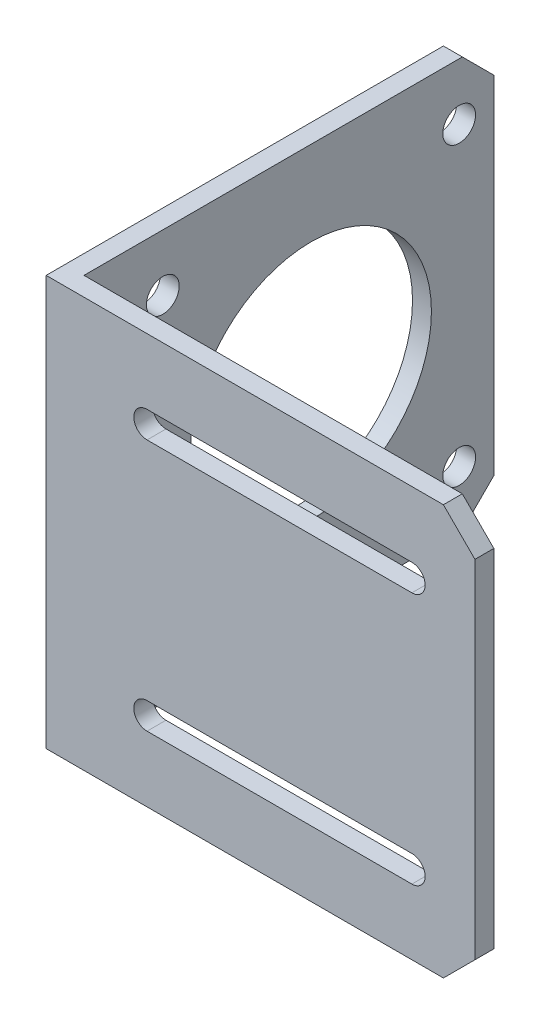
SolidWorks part; units mm, degrees
ref_plane "前视基准面" through (0, 0, 0) normal (0, 0, 1) x (1, 0, 0)
ref_plane "上视基准面" through (0, 0, 0) normal (0, 1, 0) x (1, 0, 0)
ref_plane "右视基准面" through (0, 0, 0) normal (1, 0, 0) x (0, 0, -1)
sketch "草图1" plane through (0, 0, 0) normal (0, 1, 0) x (1, 0, 0)
  line L1 (0, 0) -> (68, 0)
  line L2 (0, 0) -> (0, 3)
  line L3 (0, 3) -> (68, 3)
  line L4 (68, 0) -> (68, 3)
  line L5 (0, 3) -> (3, 3)
  line L6 (0, 3) -> (0, 68)
  line L7 (0, 68) -> (3, 68)
  line L8 (3, 3) -> (3, 68)
  dimension "D1" = 3
  dimension "D2" = 3
  dimension "D3" = 68
  dimension "D4" = 68
extrude "凸台-拉伸1" add sketch "草图1" along normal blind 65 contours L3 L8 L7 L6
sketch "草图2" plane through (0, 0, 0) normal (-1, 0, 0) x (0, 0, 1)
  line L0 (0, 32.5) -> (-39, 32.5)
  line L1 (0, 65) -> (0, 0) construction
  line L2 (-15.5, 9) -> (-15.5, 56)
  line L3 (-15.5, 9) -> (-62.5, 9)
  line L4 (-15.5, 56) -> (-62.5, 56)
  line L5 (-62.5, 9) -> (-62.5, 56)
  line L6 (-15.5, 9) -> (-62.5, 56) construction
  line L7 (-15.5, 56) -> (-62.5, 9) construction
  line L8 (-68, 65) -> (-68, 0) construction
  circle A0 centre (-39, 32.5) radius 19.1
  circle A1 centre (-62.5, 56) radius 2.6
  circle A2 centre (-62.5, 9) radius 2.6
  circle A3 centre (-15.5, 56) radius 2.6
  circle A4 centre (-15.5, 9) radius 2.6
  dimension "D2" = 38.2
  dimension "D5" = 5.2
  dimension "D6" = 5.2
  dimension "D7" = 5.2
  dimension "D8" = 5.2
  dimension "D1" = 39
  dimension "D3" = 47
  dimension "D4" = 47
  dimension "D9" = 29
extrude "切除-拉伸1" cut sketch "草图2" against normal through all contours A0 | A2 | A1 | A3 | A4
sketch "草图3" plane through (0, 0, -3) normal (0, 0, -1) x (-1, 0, 0)
  line L0 (-68, 32.5) -> (-68, 12.5)
  line L1 (-68, 65) -> (-68, 0) construction
  line L2 (-68, 12.5) -> (-16, 12.5)
  line L3 (-68, 32.5) -> (-68, 84.2912)
  line L4 (-58, 10.4) -> (-16, 10.4)
  line L5 (-16, 14.6) -> (-58, 14.6)
  circle A0 centre (-16, 12.5) radius 2.1
  circle A1 centre (-58, 12.5) radius 2.1
  dimension "D3" = 42
  dimension "D4" = 4.2
  dimension "D1" = 10
  dimension "D2" = 20
extrude "切除-拉伸2" cut sketch "草图3" against normal through all
ref_plane "基准面1" through (0, 32.5, 0) normal (0, 1, 0) x (1, 0, 0)
mirror "镜向1" about plane through (0, 32.5, 0) normal (0, 1, 0) of "切除-拉伸2"
chamfer "倒角1" distance 5 angle 45 4 edges at (68, 0, -1.5) (68, 65, -1.5) (1.5, 65, -68) (1.5, 0, -68)
